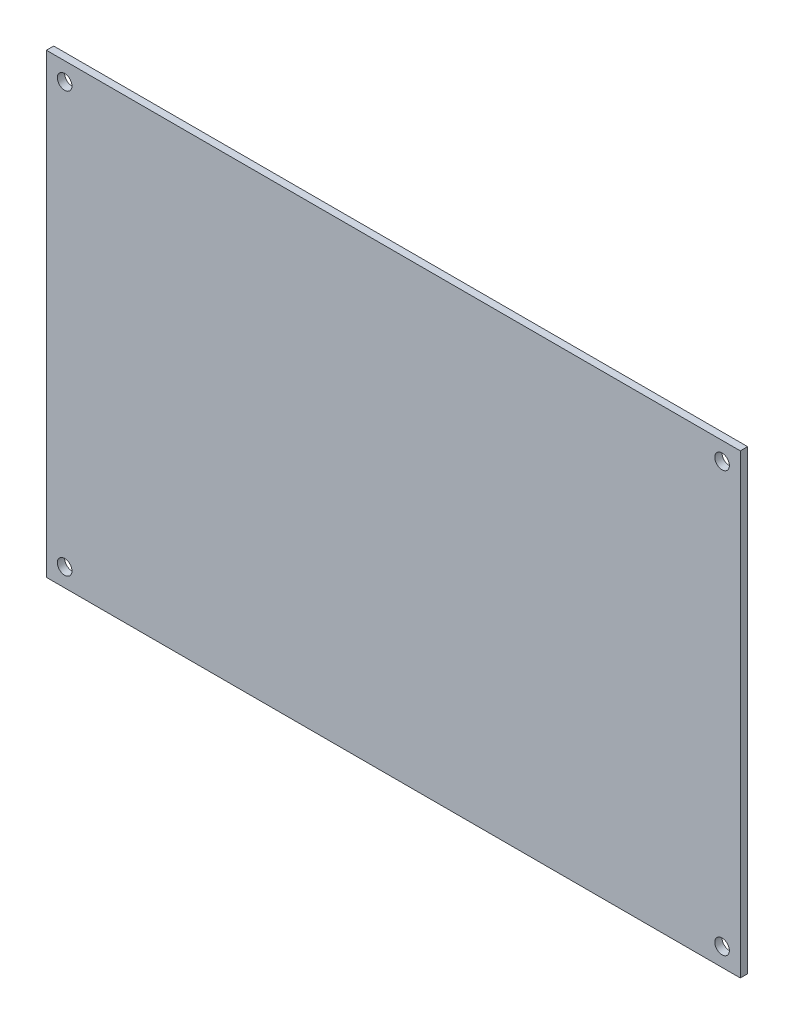
SolidWorks part; units mm, degrees
ref_plane "前视基准面" through (0, 0, 0) normal (0, 0, 1) x (1, 0, 0)
ref_plane "上视基准面" through (0, 0, 0) normal (0, 1, 0) x (1, 0, 0)
ref_plane "右视基准面" through (0, 0, 0) normal (1, 0, 0) x (0, 0, -1)
sketch "草图1" plane through (0, 0, 0) normal (0, 0, 1) x (1, 0, 0)
  line L1 (0, 0) -> (380, 0)
  line L2 (0, 0) -> (0, 250)
  line L3 (0, 250) -> (380, 250)
  line L4 (380, 0) -> (380, 250)
  circle A0 centre (10, 240) radius 4
  circle A1 centre (370, 240) radius 4
  circle A2 centre (370, 10) radius 4
  circle A3 centre (10, 10) radius 4
  dimension "D3" = 8
  dimension "D5" = 10
  dimension "D8" = 360
  dimension "D9" = 230
  dimension "D1" = 380
  dimension "D2" = 250
  dimension "D4" = 10
  dimension "D6" = 2
  dimension "D7" = 2
extrude "凸台-拉伸1" add sketch "草图1" along normal blind 4
